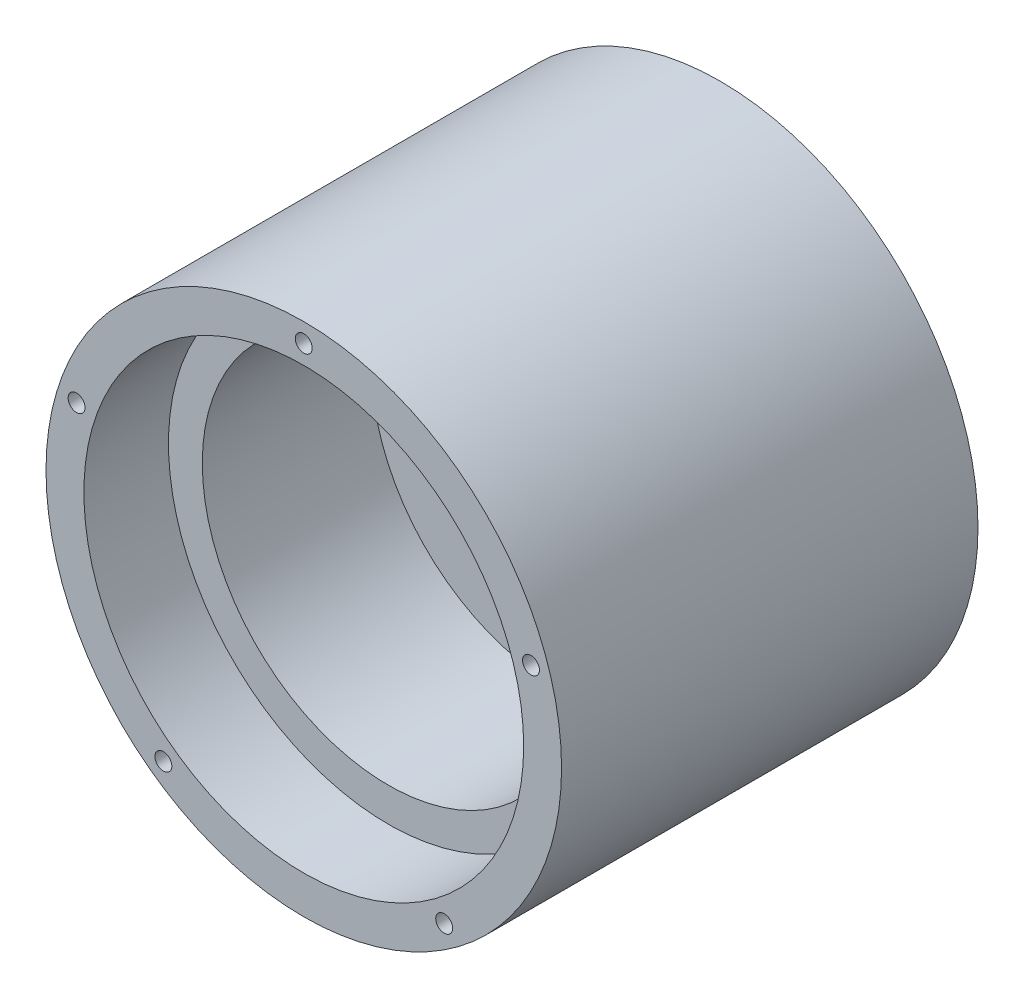
SolidWorks part; units mm, degrees
ref_plane "Front Plane" through (0, 0, 0) normal (1, 0, 0) x (0, 1, 0)
ref_plane "Top Plane" through (0, 0, 0) normal (0, 0, 1) x (0, 1, 0)
ref_plane "Right Plane" through (0, 0, 0) normal (0, 1, 0) x (-1, 0, 0)
sketch "Sketch2" plane through (0, 0, 0) normal (0, 0, 1) x (0, 1, 0)
  circle A0 centre (0, 0) radius 76.2
  dimension "D1" = 152.4
extrude "Boss-Extrude1" add sketch "Sketch2" along normal blind 85 contours A0
sketch "Sketch4" plane through (0, 0, 85) normal (0, 0, 1) x (1, 0, 0)
  circle A0 centre (0, 0) radius 65
  dimension "D1" = 130
extrude "Cut-Extrude2" cut sketch "Sketch4" against normal blind 25
sketch "Sketch5" plane through (0, 0, 60) normal (0, 0, 1) x (1, 0, 0)
  circle A0 centre (0, 0) radius 55
  dimension "D1" = 110
extrude "Cut-Extrude3" cut sketch "Sketch5" against normal blind 50
sketch "Sketch7" plane through (0, 0, 85) normal (0, 0, 1) x (1, 0, 0)
  circle A0 centre (0, 70.612) radius 2.5
  circle A1 centre (0, 0) radius 76.2 construction
  dimension "D1" = 5
  dimension "D2" = 70.612
extrude "Cut-Extrude4" cut sketch "Sketch7" against normal blind 20
pattern_circular "CirPattern1" count 5 over 360 about axis through (0, 0, 0) along (0, 0, 1) of "Cut-Extrude4"
sketch "Sketch8" plane through (0, 0, 0) normal (0, 0, -1) x (1, 0, 0)
  circle A0 centre (0, 0) radius 50.8
  circle A1 centre (0, 0) radius 76.2
  dimension "D1" = 101.6
  dimension "D2" = 152.4
extrude "Boss-Extrude2" add sketch "Sketch8" along normal blind 38.1
sketch "Sketch10" plane through (0, 0, 0) normal (0, 1, 0) x (-1, 0, 0)
  line L0 (-6.35, 0) -> (-6.35, -38.1)
  line L1 (-50.8, 0) -> (50.8, 0) construction
  line L2 (-50.8, -38.1) -> (50.8, -38.1) construction
  line L3 (-6.35, -38.1) -> (6.35, -38.1)
  line L4 (6.35, -38.1) -> (6.35, -6.35)
  line L5 (6.35, -6.35) -> (26.709, -6.35)
  line L6 (26.709, -6.35) -> (26.709, 0)
  line L7 (26.709, 0) -> (-6.35, 0)
  line L8 (0, -43.2967) -> (0, 13.2611) construction
  dimension "D1" = 6.35
  dimension "D2" = 6.35
  dimension "D3" = 6.35
extrude "Cut-Extrude5" cut sketch "Sketch10" against normal blind 66.04
pattern_circular "CirPattern2" count 4 every 90 about axis through (0, 0, 0) along (0, 0, 1) of "Cut-Extrude5"
sketch "Sketch12" plane through (0, 0, -38.1) normal (0, 0, -1) x (1, 0, 0)
  circle A2 centre (0, 0) radius 69.85
  dimension "D1" = 139.7
extrude "Cut-Extrude6" cut sketch "Sketch12" against normal blind 25.4
equation "\"o.2\"=0.187569"
